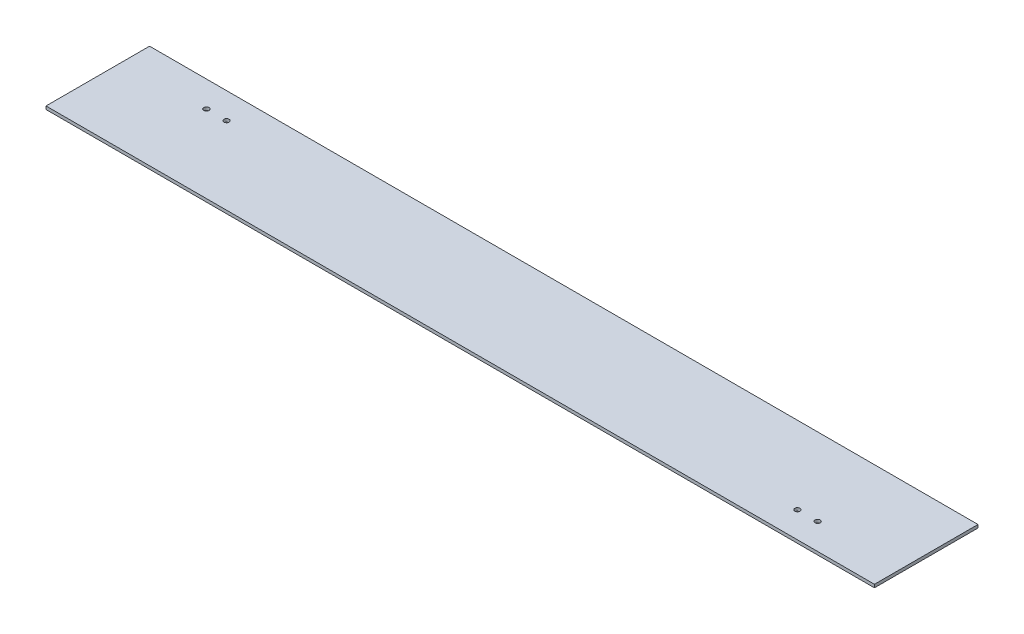
SolidWorks part; units mm, degrees
ref_plane "Front Plane" through (0, 0, 0) normal (0, 0, 1) x (1, 0, 0)
ref_plane "Top Plane" through (0, 0, 0) normal (0, 1, 0) x (1, 0, 0)
ref_plane "Right Plane" through (0, 0, 0) normal (1, 0, 0) x (0, 0, -1)
sketch "Sketch1" plane through (0, 0, 0) normal (0, 1, 0) x (1, 0, 0)
  line L1 (0, 0) -> (-800, 0)
  line L2 (0, 0) -> (0, 100)
  line L3 (0, 100) -> (-800, 100)
  line L4 (-800, 0) -> (-800, 100)
  dimension "D1" = 800
  dimension "D2" = 100
extrude "Boss-Extrude1" add sketch "Sketch1" along normal blind 3
sketch "Sketch2" plane through (0, 3, 0) normal (0, 1, 0) x (1, 0, 0)
  line L0 (-800, 100) -> (-800, 0) construction
  line L2 (0, 0) -> (0, 100) construction
  line L3 (-800, 0) -> (0, 0) construction
  line L4 (0, 100) -> (-800, 100) construction
  circle A0 centre (-80, 25.14) radius 2.5
  circle A1 centre (-99.5, 25.14) radius 2.5
  circle A2 centre (-720, 74.86) radius 2.5
  circle A3 centre (-700.5, 74.86) radius 2.5
  point P14 (0, 0)
  dimension "D1" = 5
  dimension "D2" = 5
  dimension "D6" = 80
  dimension "D7" = 5
  dimension "D12" = 5
  dimension "D3" = 19.5
  dimension "D4" = 19.5
  dimension "D5" = 80
  dimension "D8" = 0
  dimension "D9" = 25.14
  dimension "D10" = 0
  dimension "D11" = 25.14
extrude "Cut-Extrude1" cut sketch "Sketch2" against normal blind 40
